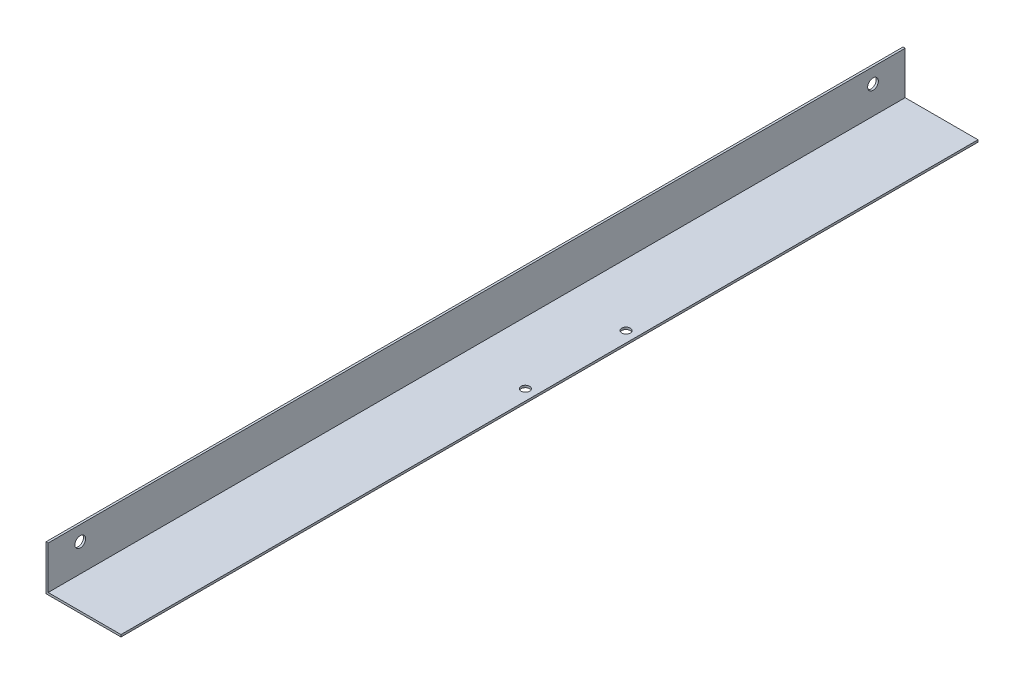
SolidWorks part; units mm, degrees
ref_plane "Plan de face" through (0, 0, 0) normal (0, 0, 1) x (1, 0, 0)
ref_plane "Plan de dessus" through (0, 0, 0) normal (0, 1, 0) x (1, 0, 0)
ref_plane "Plan de droite" through (0, 0, 0) normal (1, 0, 0) x (0, 0, -1)
sketch "Esquisse1" plane through (0, 0, 0) normal (0, 0, 1) x (1, 0, 0)
  line L0 (-1, -1) -> (-1, 20)
  line L1 (-1, 20) -> (0, 20)
  line L2 (0, 20) -> (0, 0)
  line L3 (0, 0) -> (34, 0)
  line L4 (34, 0) -> (34, -1)
  line L5 (-1, -1) -> (34, -1)
  dimension "D1" = 1
  dimension "D2" = 1
  dimension "D3" = 20
  dimension "D4" = 34
extrude "Boss.-Extru.1" add sketch "Esquisse1" along normal blind 400
sketch "Esquisse3" plane through (0, 0, 0) normal (0, 1, 0) x (1, 0, 0)
  circle A0 centre (29, -206.2603) radius 2 construction
  circle A1 centre (29, -159.2603) radius 2 construction
  circle A2 centre (29, -206.2603) radius 2
  circle A3 centre (29, -159.2603) radius 2
extrude "Enlèv. mat.-Extru.2" cut sketch "Esquisse3" against normal through all
sketch "Esquisse4" plane through (-1, 0, 0) normal (-1, 0, 0) x (0, 0, 1)
  line L0 (200, 20) -> (200, -17.9819) construction
  line L1 (400, 20) -> (0, 20) construction
  line L2 (0, 20) -> (0, -1) construction
  circle A0 centre (15, 13) radius 2.5
  circle A1 centre (385, 13) radius 2.5
  dimension "D1" = 5
  dimension "D2" = 7
  dimension "D3" = 15
extrude "Enlèv. mat.-Extru.3" cut sketch "Esquisse4" against normal blind 10
